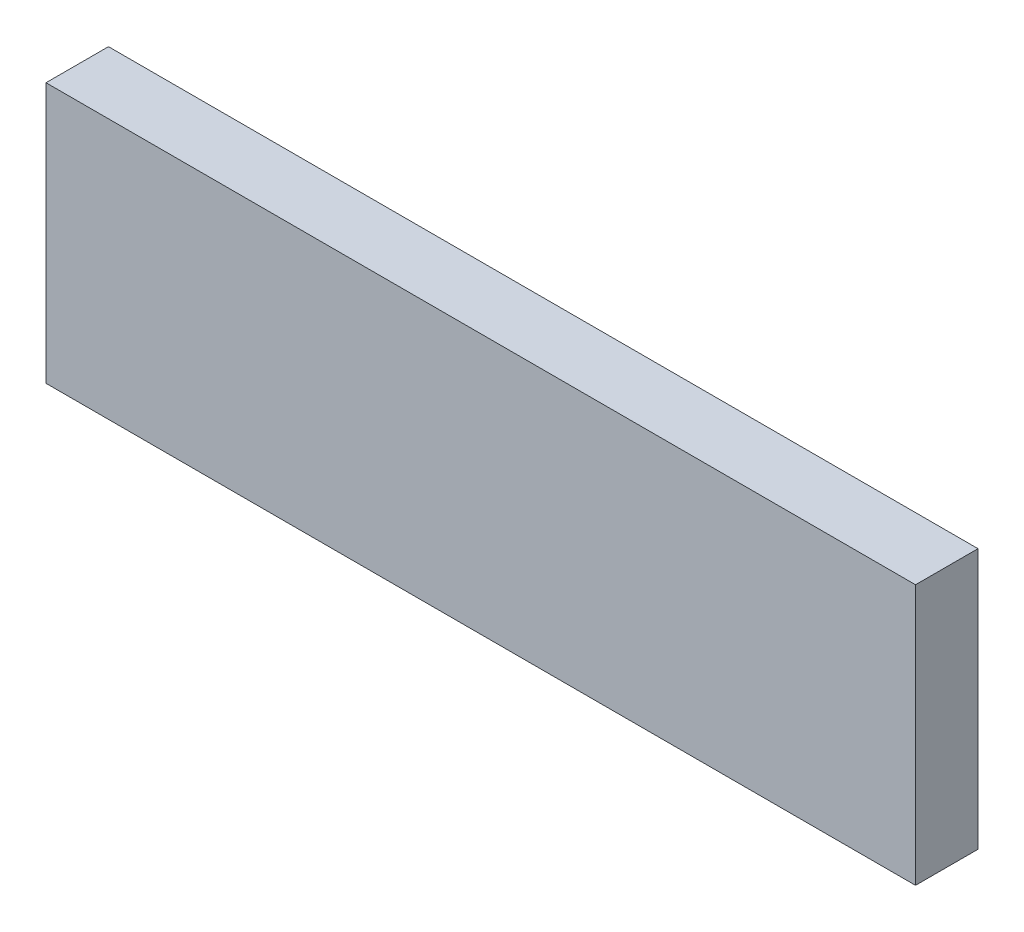
SolidWorks part; units mm, degrees
ref_plane "Plano frontal" through (0, 0, 0) normal (0, 0, 1) x (1, 0, 0)
ref_plane "Plano superior" through (0, 0, 0) normal (0, 1, 0) x (1, 0, 0)
ref_plane "Plano direito" through (0, 0, 0) normal (1, 0, 0) x (0, 0, -1)
sketch "Esboço1" plane through (0, 0, 0) normal (0, 0, 1) x (1, 0, 0)
  line L1 (-83.5, 25) -> (83.5, 25)
  line L2 (-83.5, 25) -> (-83.5, -25)
  line L3 (-83.5, -25) -> (83.5, -25)
  line L4 (83.5, 25) -> (83.5, -25)
  line L5 (-83.5, 25) -> (83.5, -25) construction
  line L6 (-83.5, -25) -> (83.5, 25) construction
  point P0 (0, 0)
extrude "Ressalto-extrusão1" add sketch "Esboço1" along normal mid plane 12
ref_plane "Plano1" through (0, -25, 0) normal (0, -1, 0) x (-1, 0, 0)
sketch "Esboço3" plane through (0, -25, 0) normal (0, -1, 0) x (-1, 0, 0)
  circle A0 centre (75, 0) radius 3
  circle A1 centre (-75, 0) radius 3
extrude "Corte-extrusão1" cut sketch "Esboço3" against normal blind 20
